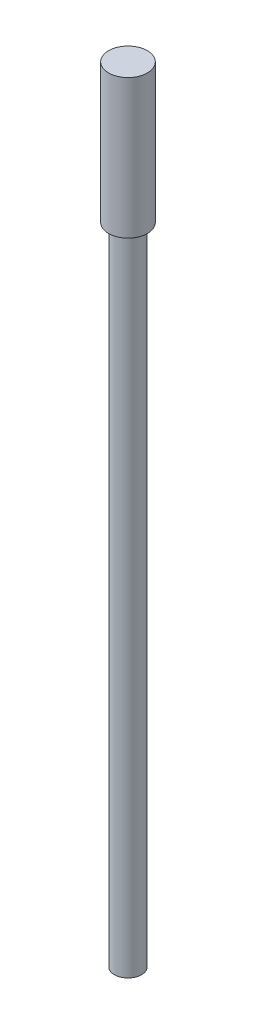
SolidWorks part; units mm, degrees
ref_plane "Спереди" through (0, 0, 0) normal (0, 0, 1) x (1, 0, 0)
ref_plane "Сверху" through (0, 0, 0) normal (0, 1, 0) x (1, 0, 0)
ref_plane "Справа" through (0, 0, 0) normal (1, 0, 0) x (0, 0, -1)
sketch "Эскиз1" plane through (0, 0, 0) normal (0, 1, 0) x (1, 0, 0)
  circle A0 centre (0, 0) radius 10.75
  circle A1 centre (0, 0) radius 7.75
  dimension "D1" = 21.5
  dimension "D2" = 3
extrude "Бобышка-Вытянуть1" add sketch "Эскиз1" along normal blind 620
sketch "Эскиз2" plane through (0, 620, 0) normal (0, 1, 0) x (1, 0, 0)
  circle A0 centre (0, 0) radius 15.3016
extrude "Бобышка-Вытянуть2" add sketch "Эскиз2" against normal blind 110
